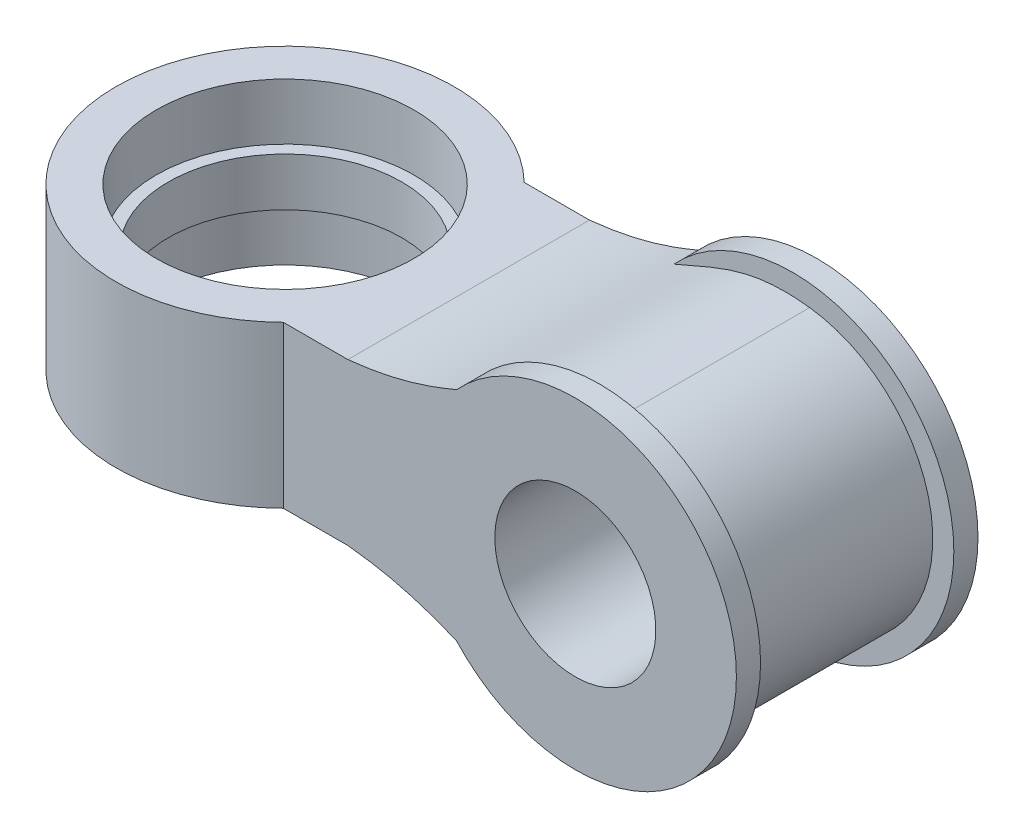
SolidWorks part; units mm, degrees
ref_plane "Front Plane" through (0, 0, 0) normal (0, 0, 1) x (1, 0, 0)
ref_plane "Top Plane" through (0, 0, 0) normal (0, 1, 0) x (1, 0, 0)
ref_plane "Right Plane" through (0, 0, 0) normal (1, 0, 0) x (0, 0, -1)
sketch "Sketch1" plane through (0, 0, 0) normal (0, 0, 1) x (1, 0, 0)
  circle A0 centre (0, 0) radius 20
  dimension "D1" = 40
extrude "Boss-Extrude1" add sketch "Sketch1" along normal blind 3
sketch "Sketch2" plane through (0, 0, 0) normal (0, 0, -1) x (-1, 0, 0)
  line L0 (28.2445, 10) -> (12.9903, 11.5555) construction
  line L2 (-40, 10) -> (-40, -10)
  line L4 (40, 10) -> (40, -10)
  line L7 (12.9903, 11.5555) -> (9.9009, 18.7195) construction
  line L8 (9.9009, 18.7195) -> (-2.1006, 17.2588) construction
  line L9 (17.3861, 0) -> (44.0239, 0) construction
  line L10 (28.2445, -10) -> (12.9903, -11.5555) construction
  line L11 (12.9903, -11.5555) -> (9.9009, -18.7195) construction
  line L12 (9.9009, -18.7195) -> (-2.1006, -17.2588) construction
  line L13 (28.2445, 10) -> (40, 10)
  line L15 (16.867, 4.2168) -> (40, 10) construction
  line L16 (28.2445, -10) -> (40, -10)
  arc A0 (-2.1006, 17.2588) -> (-2.1006, -17.2588) centre (0, 0) ccw
  spline S0 degree 3 poles (28.2445, 10) (12.9903, 11.5555) (9.9009, 18.7195) (-2.1006, 17.2588) knots 0 0 0 0 1 1 1 1
  spline S1 degree 3 poles (28.2445, -10) (12.9903, -11.5555) (9.9009, -18.7195) (-2.1006, -17.2588) knots 0 0 0 0 1 1 1 1
  point P0 (0, 0)
  circle M7 centre (0, 0) radius 20
  dimension "D1" = 20
  dimension "D2" = 80
extrude "Boss-Extrude2" add sketch "Sketch2" against normal blind 30 contours S1 S0 A0 M7 | S1 L16 L4 L13 S0 M7
sketch "Sketch3" plane through (0, 0, 30) normal (0, 0, 1) x (1, 0, 0)
  circle A0 centre (0, 0) radius 20
  dimension "D1" = 40
extrude "Boss-Extrude3" add sketch "Sketch3" against normal blind 3
sketch "Sketch4" plane through (0, 0, 0) normal (0, 0, -1) x (-1, 0, 0)
  circle A0 centre (0, 0) radius 10
  dimension "D1" = 20
extrude "Cut-Extrude1" cut sketch "Sketch4" against normal blind 43
sketch "Sketch6" plane through (0, 10, 0) normal (0, 1, 0) x (1, 0, 0)
  line L0 (-40, -30) -> (-40, 0) construction
  circle A0 centre (-51, -15.0439) radius 21
  circle A1 centre (-51, -15.0439) radius 16
  point P5 (-40, -15)
  dimension "D1" = 42
  dimension "D3" = 32
  dimension "D2" = 11
extrude "Boss-Extrude4" add sketch "Sketch6" against normal blind 20
sketch "Sketch7" plane through (0, 10, 0) normal (0, 1, 0) x (1, 0, 0)
  circle A0 centre (-51, -15.0439) radius 16
extrude "Cut-Extrude2" cut sketch "Sketch7" against normal blind 20
sketch "Sketch8" plane through (0, 0, 0) normal (0, 1, 0) x (1, 0, 0)
  circle A0 centre (-51, -15.0439) radius 21
  circle A1 centre (-51, -15.0439) radius 14.5
  dimension "D1" = 29
extrude "Boss-Extrude5" add sketch "Sketch8" along normal blind 3 and the other way blind 3
